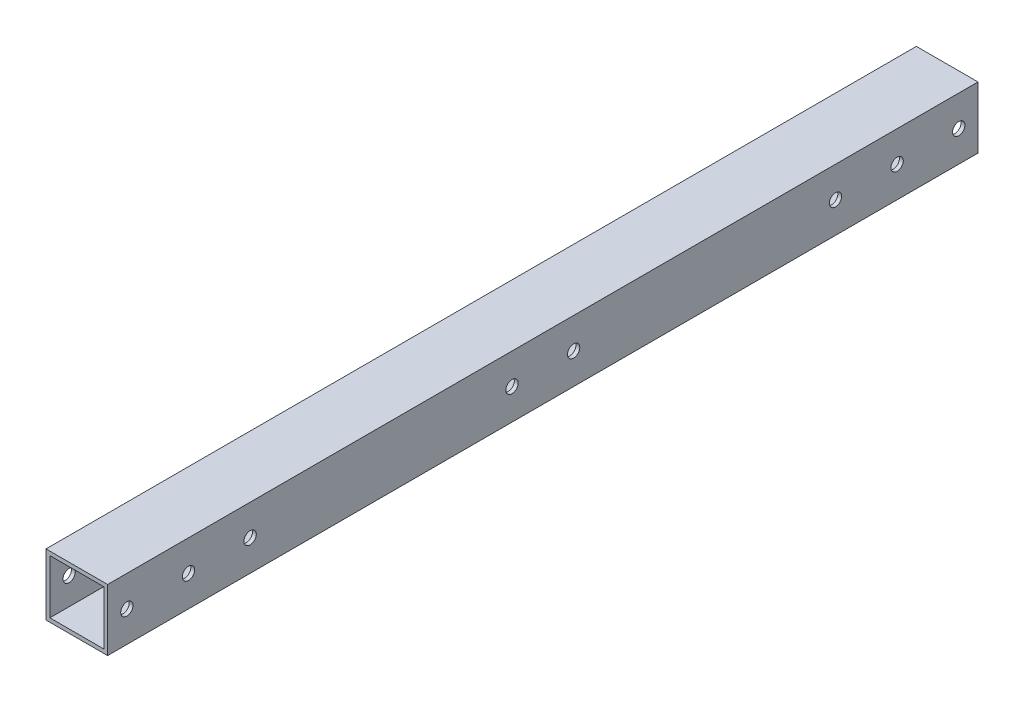
SolidWorks part; units mm, degrees
ref_plane "Front Plane" through (0, 0, 0) normal (0, 0, 1) x (1, 0, 0)
ref_plane "Top Plane" through (0, 0, 0) normal (0, 1, 0) x (1, 0, 0)
ref_plane "Right Plane" through (0, 0, 0) normal (1, 0, 0) x (0, 0, -1)
sketch "Sketch1" plane through (0, 0, 0) normal (0, 0, 1) x (1, 0, 0)
  line L1 (0, 0) -> (25.4, 0)
  line L2 (0, 0) -> (0, 25.4)
  line L3 (0, 25.4) -> (25.4, 25.4)
  line L4 (25.4, 0) -> (25.4, 25.4)
  line L5 (1.5875, 1.5875) -> (23.8125, 1.5875)
  line L6 (1.5875, 1.5875) -> (1.5875, 23.8125)
  line L7 (1.5875, 23.8125) -> (23.8125, 23.8125)
  line L8 (23.8125, 1.5875) -> (23.8125, 23.8125)
  dimension "D1" = 25.4
  dimension "D2" = 1.5875
  dimension "D3" = 1.5875
  dimension "D4" = 1.5875
  dimension "D5" = 1.5875
extrude "Boss-Extrude1" add sketch "Sketch1" along normal blind 358.775
sketch "Sketch4" plane through (25.4, 0, 0) normal (1, 0, 0) x (0, 0, -1)
  line L0 (-358.775, 25.4) -> (0, 25.4) construction
  line L1 (-358.775, 0) -> (-358.775, 25.4) construction
  line L2 (-179.3875, 25.4) -> (-179.3875, 0) construction
  line L3 (-358.775, 0) -> (0, 0) construction
  circle A0 centre (-350.8375, 12.7) radius 2.54
  circle A2 centre (-325.4375, 12.7) radius 2.54
  circle A3 centre (-300.0375, 12.7) radius 2.54
  circle A11 centre (-58.7375, 12.7) radius 2.54
  circle A12 centre (-33.3375, 12.7) radius 2.54
  circle A13 centre (-7.9375, 12.7) radius 2.54
  circle A14 centre (-192.0875, 12.7) radius 2.54
  circle A15 centre (-166.6875, 12.7) radius 2.54
  dimension "D1" = 5.08
  dimension "D2" = 12.7
  dimension "D3" = 7.9375
  dimension "D4" = 3
  dimension "D5" = 12.7
extrude "Cut-Extrude3" cut sketch "Sketch4" against normal through all
